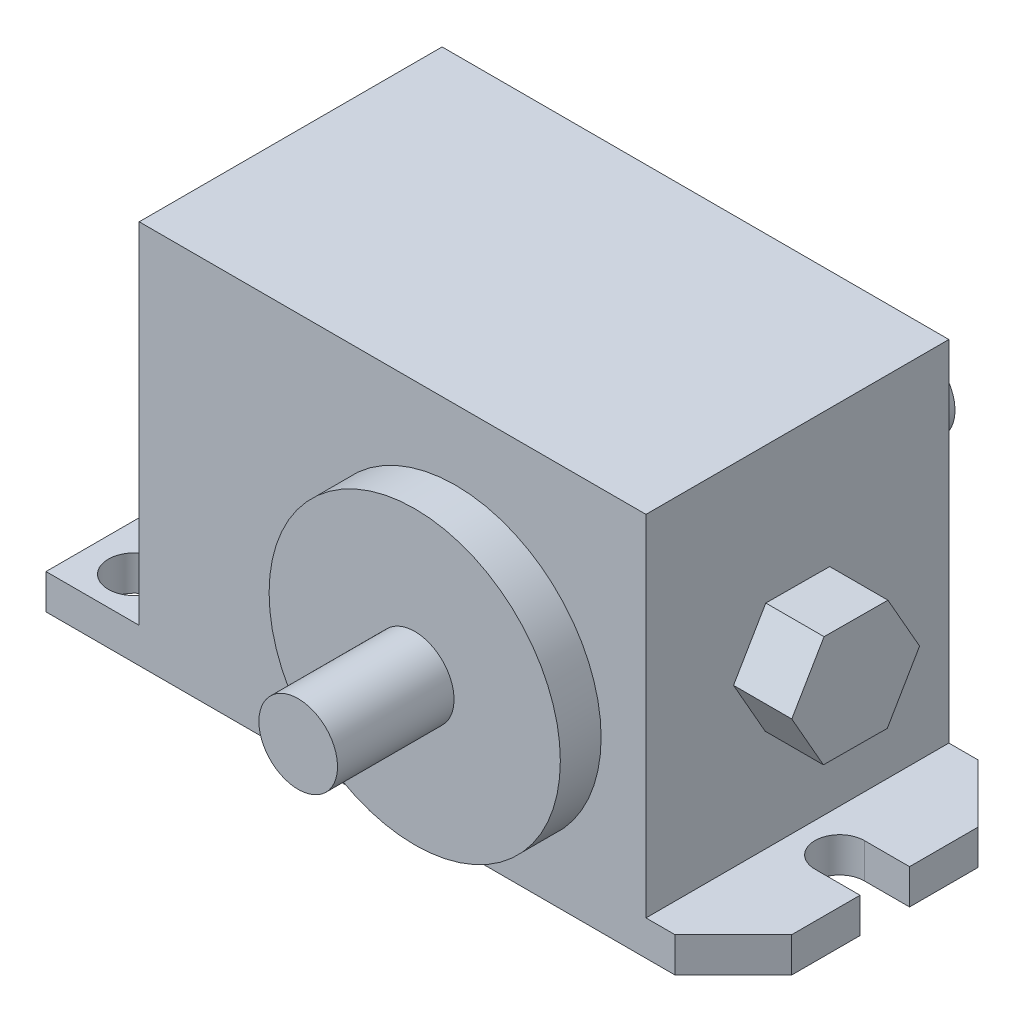
SolidWorks part; units mm, degrees
ref_plane "Płaszczyzna przednia" through (0, 0, 0) normal (0, 0, 1) x (1, 0, 0)
ref_plane "Płaszczyzna górna" through (0, 0, 0) normal (0, 1, 0) x (1, 0, 0)
ref_plane "Płaszczyzna prawa" through (0, 0, 0) normal (1, 0, 0) x (0, 0, -1)
sketch "Szkic1" plane through (0, 0, 0) normal (0, 1, 0) x (1, 0, 0)
  line L0 (54, 26) -> (64, 16)
  line L1 (-54, 26) -> (54, 26)
  line L2 (-54, 26) -> (-54, -26)
  line L3 (-54, -26) -> (54, -26)
  line L4 (64, 16) -> (64, -16)
  line L5 (54, -26) -> (64, -16)
  line L6 (64, 4.25) -> (56.25, 4.25)
  line L7 (56.25, -4.25) -> (64, -4.25)
  line L8 (-46, 18.8) -> (-46, -18.8) construction
  arc A0 (56.25, 4.25) -> (56.25, -4.25) centre (56.25, 0) ccw
  circle A1 centre (-46, 18.8) radius 4.5
  circle A2 centre (-46, -18.8) radius 4.5
  point P1 (64, -26)
  point P3 (64, 26)
  point P6 (-54, 0)
  point P10 (0, 26)
  point P15 (64, 0)
  point P21 (-46, 0)
  point P22 (-46, 18.6649)
  dimension "D3" = 4.25
  dimension "D7" = 9
  dimension "D8" = 9
  dimension "D1" = 118
  dimension "D2" = 52
  dimension "D4" = 7.75
  dimension "D9" = 8
  dimension "D10" = 7.2
extrude "Dodanie-wyciągnięcie1" add sketch "Szkic1" along normal blind 6
sketch "Szkic2" plane through (0, 6, 0) normal (0, 1, 0) x (1, 0, 0)
  line L0 (-54, 26) -> (54, 26) construction
  line L1 (-38, 26) -> (49, 26)
  line L2 (-38, 26) -> (-38, -26)
  line L3 (-38, -26) -> (49, -26)
  line L4 (49, 26) -> (49, -26)
  line L5 (-54, -26) -> (54, -26) construction
  line L6 (-54, 26) -> (-54, -26) construction
  dimension "D1" = 87
  dimension "D2" = 16
extrude "Dodanie-wyciągnięcie2" add sketch "Szkic2" along normal blind 60
sketch "Szkic3" plane through (0, 0, -26) normal (0, 0, -1) x (-1, 0, 0)
  line L0 (-49, 66) -> (-49, 6) construction
  line L1 (-49, 66) -> (38, 66) construction
  circle A0 centre (-16.3, 29) radius 25
  dimension "D1" = 50
  dimension "D2" = 32.7
  dimension "D3" = 37
extrude "Dodanie-wyciągnięcie3" add sketch "Szkic3" along normal blind 7
sketch "Szkic4" plane through (0, 0, -33) normal (0, 0, -1) x (-1, 0, 0)
  circle A0 centre (-16.3, 29) radius 6.75
  dimension "D1" = 13.5
extrude "Dodanie-wyciągnięcie4" add sketch "Szkic4" along normal blind 20
mirror "Lustro1" about plane through (0, 0, 0) normal (0, 0, 1) of "Dodanie-wyciągnięcie4", "Dodanie-wyciągnięcie3"
sketch "Szkic5" plane through (49, 0, 0) normal (1, 0, 0) x (0, 0, -1)
  line L0 (-26, 66) -> (26, 66) construction
  line L1 (5.4289, 23.4679) -> (10.9695, 32.9355)
  line L2 (10.9695, 32.9355) -> (5.5406, 42.4676)
  line L3 (5.5406, 42.4676) -> (-5.4289, 42.5321)
  line L4 (-5.4289, 42.5321) -> (-10.9695, 33.0645)
  line L5 (-10.9695, 33.0645) -> (-5.5406, 23.5324)
  line L6 (-5.5406, 23.5324) -> (5.4289, 23.4679)
  circle A0 centre (0, 33) radius 9.5 construction
  point P10 (0, 0)
  point P12 (5.5406, 23.5324)
  point P13 (0, 0)
  dimension "D1" = 33
  dimension "D2" = 19
  dimension "D3" = 33.0645
extrude "Dodanie-wyciągnięcie5" add sketch "Szkic5" along normal blind 10
